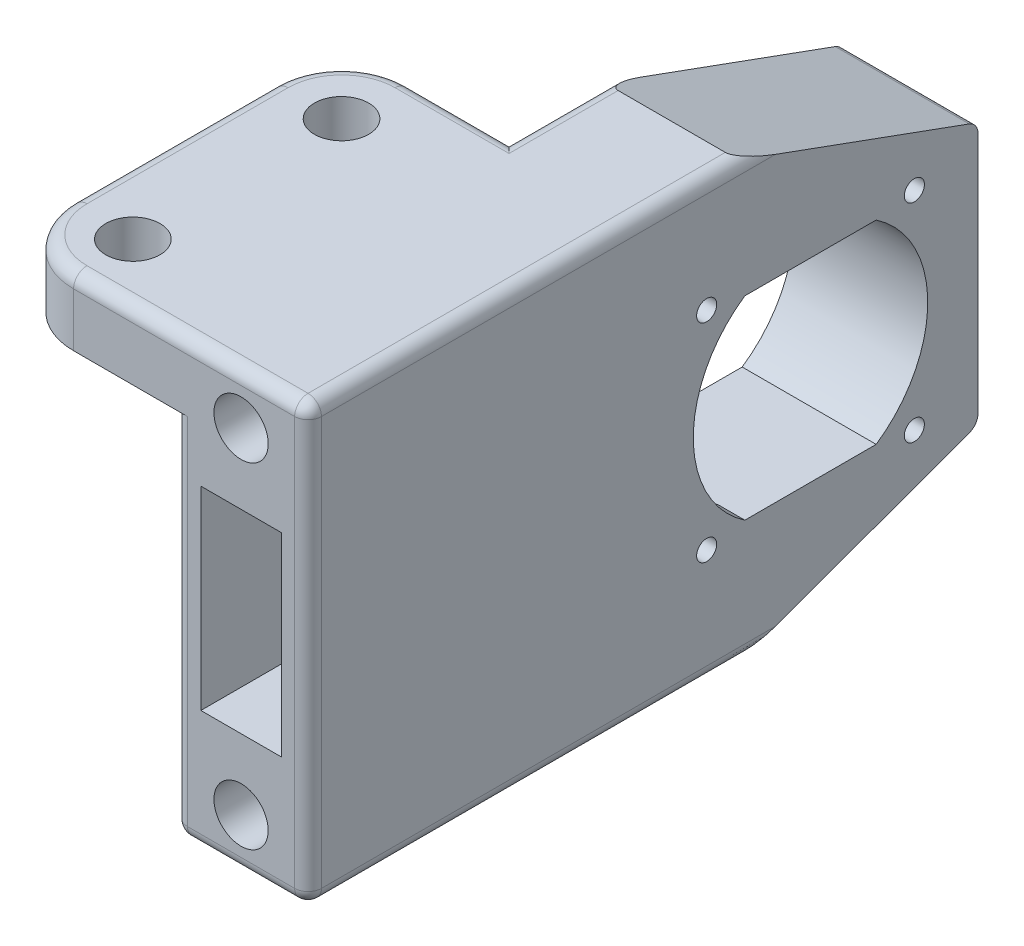
SolidWorks part; units mm, degrees
ref_plane "Front (XY)" through (0, 0, 0) normal (0, 0, 1) x (1, 0, 0)
ref_plane "Top (XZ)" through (0, 0, 0) normal (0, 1, 0) x (1, 0, 0)
ref_plane "Right (YZ)" through (0, 0, 0) normal (1, 0, 0) x (0, 0, -1)
sketch "Sketch1" plane through (0, 0, 0) normal (0, 1, 0) x (1, 0, 0)
  circle A0 centre (0, 0) radius 4.05
  circle A1 centre (0, -31.15) radius 4.05
  dimension "D1" = 8.1
  dimension "D2" = 31.15
sketch "Sketch2" plane through (0, 0, 0) normal (0, 1, 0) x (1, 0, 0)
  circle A1 centre (0, 0) radius 10
  dimension "D1" = 20
extrude "Boss-Extrude1" add sketch "Sketch2" against normal blind 65
sketch "Sketch3" plane through (0, 0, 0) normal (0, 1, 0) x (1, 0, 0)
  line L0 (-10, 0) -> (-10, -40)
  line L1 (-10, -40) -> (15, -40)
  line L2 (15, -40) -> (15, 10)
  line L3 (15, 10) -> (0, 10)
  circle A0 centre (0, 0) radius 10 construction
  arc A1 (0, 10) -> (-10, 0) centre (0, 0) ccw
  dimension "D1" = 15
  dimension "D2" = 40
  dimension "D3" = 25
  dimension "D4" = 50
extrude "Boss-Extrude2" add sketch "Sketch3" against normal blind 10
sketch "Sketch4" plane through (0, 0, 0) normal (0, 1, 0) x (1, 0, 0)
  line L0 (15, 10) -> (0, 10) construction
  line L1 (15, 10) -> (0, 10)
  line L2 (15, -40) -> (15, 10) construction
  line L3 (15, -10) -> (15, 10)
  line L4 (0, -10) -> (15, -10)
  arc A0 (-10, 0) -> (0, 10) centre (0, 0) ccw construction
  arc A1 (0, -10) -> (0, 10) centre (0, 0) ccw
extrude "Boss-Extrude3" add sketch "Sketch4" against normal up to surface (65 mm away) up to face at (0, -65, 10)
fillet "Fillet1" radius 10 1 edges at (-10, -5, 40)
sketch "Sketch5" plane through (0, 0, 0) normal (0, 1, 0) x (1, 0, 0)
  circle A0 centre (0, -31.15) radius 4.05 construction
  circle A1 centre (0, 0) radius 4.05 construction
  circle A2 centre (0, -31.15) radius 4.05
  circle A3 centre (0, 0) radius 4.05
extrude "Cut-Extrude1" cut sketch "Sketch5" against normal through all
sketch "Sketch6" plane through (0, 0, 0) normal (0, 1, 0) x (1, 0, 0)
  line L0 (15, -40) -> (35, -40)
  line L1 (35, -40) -> (35, 60)
  line L2 (35, 60) -> (15, 60)
  line L3 (15, 60) -> (15, 10)
  line L4 (15, -40) -> (15, 10) construction
  line L5 (15, -40) -> (15, 10)
  dimension "D1" = 100
  dimension "D2" = 20
extrude "Boss-Extrude4" add sketch "Sketch6" against normal up to surface (65 mm away) up to face at (0, -65, 4.05)
sketch "Sketch8" plane through (0, 0, 40) normal (0, 0, 1) x (1, 0, 0)
  line L0 (0, 0) -> (35, 0) construction
  circle A0 centre (25, -7.5) radius 4.05
  circle A1 centre (25, -57.5) radius 4.05
  dimension "D1" = 8.1
  dimension "D2" = 50
  dimension "D3" = 7.5
  dimension "D4" = 25
extrude "Cut-Extrude3" cut sketch "Sketch8" against normal blind 50
sketch "Sketch9" plane through (15, 0, 0) normal (-1, 0, 0) x (0, 0, 1)
  line L0 (-35, -65) -> (-35, -32.5) construction
  line L1 (-10, -65) -> (-60, -65) construction
  dimension "D1" = 32.5
sketch "Sketch12" plane through (15, 0, 0) normal (-1, 0, 0) x (0, 0, 1)
  circle A0 centre (-35, -32.5) radius 17.5
  dimension "D1" = 35
sketch "Sketch13" plane through (15, 0, 0) normal (-1, 0, 0) x (0, 0, 1)
  line L4 (-60, -18) -> (-10, -18)
  line L5 (-44.798, -18) -> (-25.202, -18)
  line L7 (-10, -47) -> (-60, -47)
  line L8 (-25.202, -47) -> (-44.798, -47)
  circle A0 centre (-35, -32.5) radius 17.5 construction
  arc A1 (-44.798, -18) -> (-44.798, -47) centre (-35, -32.5) ccw
  arc A2 (-25.202, -47) -> (-25.202, -18) centre (-35, -32.5) ccw
  dimension "D1" = 18
  dimension "D2" = 18
extrude "Cut-Extrude5" cut sketch "Sketch13" against normal through all
sketch "Sketch7" plane through (0, 0, 40) normal (0, 0, 1) x (1, 0, 0)
  line L0 (19, -18) -> (19, -47)
  line L1 (19, -47) -> (31, -47)
  line L2 (31, -47) -> (31, -18)
  line L3 (31, -18) -> (19, -18)
  line L4 (0, 0) -> (35, 0) construction
  point P4 (25, -18)
  dimension "D1" = 29
  dimension "D2" = 12
  dimension "D3" = 25
  dimension "D4" = 18
extrude "Cut-Extrude6" cut sketch "Sketch7" against normal up to surface (84.798 mm away)
chamfer "Chamfer1" distance 13 angle 70 2 edges at (25, -65, -60) (25, 0, -60)
fillet "Fillet2" radius 2 19 edges at (7.5, -65, 10) (-10, -65, 0) (17.5, 0, 40) (-7.0711, 0, 37.0711) (-10, 0, 15) (-7.0711, 0, -7.0711) (35, -32.5, 40) (15, -37.5, 40) (25, -65, 40) (35, -65, 7.8586) (15, -65, 25) (15, -65, -17.1414) (7.5, 0, -10) (7.5, -65, -10) (25, -65, -24.2828) (25, -52, -60) (25, -13, -60) (15, 0, -17.1414) (35, 0, 7.8586)
sketch "Sketch14" plane through (35, 0, 0) normal (1, 0, 0) x (0, 0, -1)
  circle A0 centre (19.5, -17) radius 1.5
  circle A1 centre (50.5, -17) radius 1.5
  circle A2 centre (50.5, -48) radius 1.5
  circle A3 centre (19.5, -48) radius 1.5
  point P8 (0, 0)
  point P9 (0, 0)
  dimension "D1" = 3
  dimension "D2" = 31
  dimension "D3" = 31
  dimension "D4" = 15.5
  dimension "D5" = 15.5
extrude "Cut-Extrude7" cut sketch "Sketch14" against normal through all
